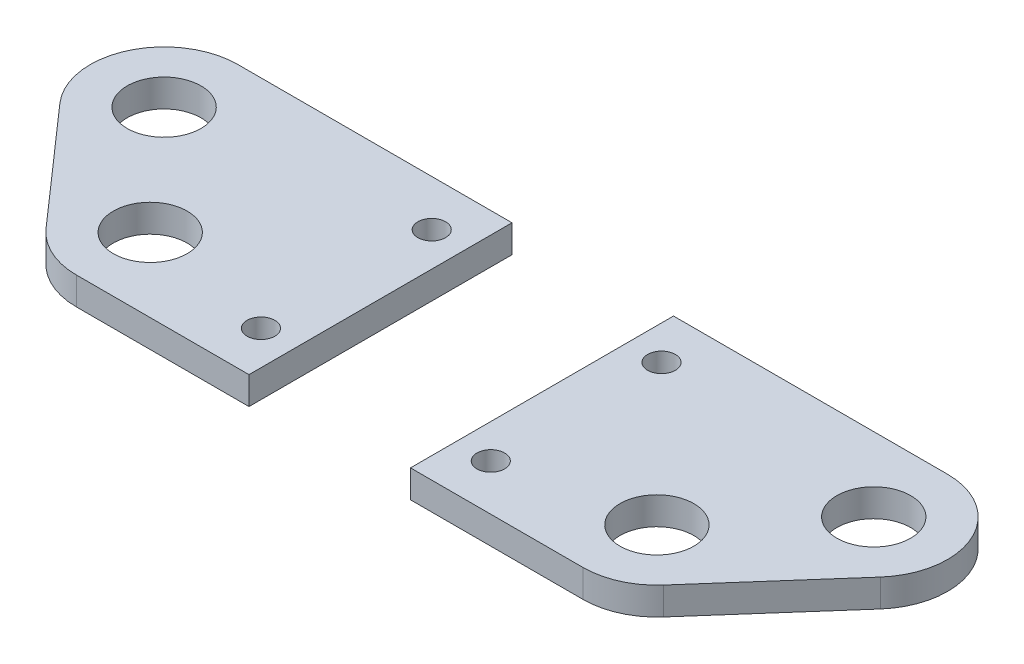
SolidWorks part; units mm, degrees
material "Chipboard"
ref_plane "Front Plane" through (0, 0, 0) normal (0, 0, 1) x (1, 0, 0)
ref_plane "Top Plane" through (0, 0, 0) normal (0, 1, 0) x (1, 0, 0)
ref_plane "Right Plane" through (0, 0, 0) normal (1, 0, 0) x (0, 0, -1)
sketch "Sketch1" plane through (0, 0, 0) normal (0, 1, 0) x (1, 0, 0)
  line L0 (-12.45, 10.75) -> (-38.45, 10.75) construction
  line L1 (-27.45, -14.25) -> (-8.75, -14.25)
  line L2 (-12.45, -10.75) -> (-27.45, -10.75) construction
  line L3 (0, 6.25) -> (0, -6.6749) construction
  line L4 (12.45, 9.25) -> (12.45, -9.25) construction
  line L5 (-8.3494, -0.3251) -> (-12.2494, -0.3251) construction
  line L6 (-8.3494, 9.25) -> (-12.45, 9.25) construction
  line L7 (8.3494, -9.25) -> (12.45, -9.25) construction
  line L8 (8.3494, 9.25) -> (12.45, 9.25) construction
  line L9 (8.3494, -0.3251) -> (12.2494, -0.3251) construction
  line L10 (-33.4557, -11.535) -> (-44.4557, 0.965)
  line L11 (12.45, -10.75) -> (27.45, -10.75) construction
  line L12 (12.45, 10.75) -> (38.45, 10.75) construction
  line L13 (8.75, 14.25) -> (8.75, -14.25)
  line L14 (-38.45, 6.25) -> (0, 6.25) construction
  line L15 (38.45, 14.25) -> (8.75, 14.25)
  line L16 (-38.45, 14.25) -> (-8.75, 14.25)
  line L17 (33.4557, -11.535) -> (44.4557, 0.965)
  line L18 (27.45, -14.25) -> (8.75, -14.25)
  line L20 (-8.75, 14.25) -> (-8.75, -14.25)
  line L22 (-8.3494, -9.25) -> (-12.45, -9.25) construction
  line L25 (-12.45, 9.25) -> (-12.45, -9.25) construction
  circle A0 centre (-12.45, 9.25) radius 1.5
  circle A1 centre (-12.45, -9.25) radius 1.5
  arc A2 (38.45, 14.25) -> (44.4557, 0.965) centre (38.45, 6.25) cw
  circle A3 centre (27.45, -6.25) radius 4.5
  circle A4 centre (38.45, 6.25) radius 4.5
  arc A5 (-33.4557, -11.535) -> (-27.45, -14.25) centre (-27.45, -6.25) ccw
  circle A6 centre (-38.45, 6.25) radius 4.5
  arc A7 (33.4557, -11.535) -> (27.45, -14.25) centre (27.45, -6.25) cw
  circle A8 centre (-27.45, -6.25) radius 4.5
  circle A9 centre (12.45, -9.25) radius 1.5
  circle A10 centre (12.45, 9.25) radius 1.5
  arc A13 (-38.45, 14.25) -> (-44.4557, 0.965) centre (-38.45, 6.25) ccw
  point P5 (-12.45, 0)
  dimension "D2" = 9
  dimension "D7" = 8
  dimension "D8" = 16
  dimension "D13" = 18.5
  dimension "D15" = 3
  dimension "D16" = 3
  dimension "D4" = 9
  dimension "D3" = 17.5
  dimension "D5" = 24.9
  dimension "D6" = 15
  dimension "D14" = 12.45
  dimension "D17" = 12.45
  dimension "D24" = 26
  dimension "D25" = 8.75
  dimension "D26" = 3.7
extrude "Boss-Extrude1" add sketch "Sketch1" along normal blind 3
sketch "Sketch2" plane through (0, 3, 0) normal (0, 1, 0) x (1, 0, 0)
  line L0 (-12.45, -4.75) -> (-8.75, -4.75)
  line L1 (-12.45, 4.75) -> (-8.75, 4.75)
  line L2 (-17.8583, 11.25) -> (-25.9502, 11.25)
  line L3 (-38.45, 14.25) -> (-12.45, 0)
  line L4 (-8.75, 14.25) -> (-38.45, 14.25)
  line L5 (-44.4557, 0.965) -> (-33.4557, -11.535)
  line L6 (-27.45, -14.25) -> (-8.75, -14.25)
  line L7 (-8.75, -14.25) -> (-8.75, 14.25)
  line L8 (-8.75, 14.25) -> (-38.45, 14.25)
  line L9 (-44.4557, 0.965) -> (-33.4557, -11.535)
  line L10 (-27.45, -14.25) -> (-8.75, -14.25)
  line L11 (-8.75, -14.25) -> (-8.75, 14.25)
  line L12 (-17.8583, -9.25) -> (-19.3877, -9.25)
  line L13 (-12.45, -13.75) -> (-8.75, -13.75)
  line L14 (0, 0) -> (0, -14.25) construction
  line L15 (26.4308, 9.3731) -> (19.0823, 5.3455)
  line L16 (-28.972, 7.3448) -> (-20.5242, 2.7148)
  line L17 (-26.4308, 9.3731) -> (-19.0823, 5.3455)
  line L18 (28.972, 7.3448) -> (20.5242, 2.7148)
  line L19 (-37.7291, 15.5654) -> (-11.7291, 1.3154) construction
  line L20 (-8.75, 11.25) -> (-38.45, 11.25) construction
  line L21 (-39.1709, 12.9346) -> (-13.1709, -1.3154) construction
  line L22 (12.45, -13.75) -> (8.75, -13.75)
  line L23 (17.8583, -9.25) -> (19.3877, -9.25)
  line L24 (8.75, -14.25) -> (8.75, 14.25)
  line L25 (27.45, -14.25) -> (8.75, -14.25)
  line L26 (44.4557, 0.965) -> (33.4557, -11.535)
  line L27 (8.75, 14.25) -> (38.45, 14.25)
  line L28 (38.45, 14.25) -> (12.45, 0)
  line L29 (17.8583, 11.25) -> (25.9502, 11.25)
  line L30 (12.45, 4.75) -> (8.75, 4.75)
  line L31 (12.45, -4.75) -> (8.75, -4.75)
  circle A0 centre (-12.45, 9.25) radius 1.5 construction
  circle A1 centre (-12.45, 9.25) radius 1.5
  arc A2 (-38.45, 14.25) -> (-44.4557, 0.965) centre (-38.45, 6.25) ccw
  arc A3 (-33.4557, -11.535) -> (-27.45, -14.25) centre (-27.45, -6.25) ccw
  arc A4 (-38.45, 14.25) -> (-44.4557, 0.965) centre (-38.45, 6.25) ccw
  arc A5 (-33.4557, -11.535) -> (-27.45, -14.25) centre (-27.45, -6.25) ccw
  circle A6 centre (-12.45, -9.25) radius 1.5 construction
  circle A7 centre (-12.45, -9.25) radius 1.5
  circle A8 centre (-27.45, -6.25) radius 4.5 construction
  circle A9 centre (-27.45, -6.25) radius 4.5
  circle A10 centre (-38.45, 6.25) radius 4.5 construction
  circle A11 centre (-38.45, 6.25) radius 4.5
  arc A12 (-16.875, 10.0682) -> (-16.6017, 7.5141) centre (-12.45, 9.25) ccw
  arc A13 (-16.875, -10.0682) -> (-12.45, -13.75) centre (-12.45, -9.25) ccw
  arc A14 (-12.45, 4.75) -> (-12.45, -4.75) centre (-12.45, 0) ccw
  arc A15 (-21.8919, -0.4961) -> (-30.0576, 1.3131) centre (-27.45, -6.25) ccw
  arc A16 (-31.7065, 10.554) -> (-35.8424, -1.3131) centre (-38.45, 6.25) ccw
  arc A17 (-16.9444, 6.3137) -> (-17.8986, 5.5113) centre (-12.45, 0) ccw
  arc A18 (-20.0271, 1.6278) -> (-20.1975, 0.1977) centre (-12.45, 0) ccw
  arc A19 (-30.4523, 6.4437) -> (-28.972, 7.3448) centre (-29.4526, 6.4679) cw
  arc A20 (-12.45, 7.75) -> (-12.45, -7.75) centre (-12.45, 0) ccw construction
  arc A21 (-25.9502, 11.25) -> (-26.4308, 9.3731) centre (-25.9502, 10.25) ccw
  arc A22 (-17.8986, 5.5113) -> (-19.0823, 5.3455) centre (-18.6017, 6.2225) cw
  arc A23 (-20.0271, 1.6278) -> (-20.5242, 2.7148) centre (-21.0048, 1.8378) ccw
  arc A24 (-16.6017, 7.5141) -> (-16.9444, 6.3137) centre (-17.5243, 7.1284) cw
  circle A25 centre (-12.45, 9.25) radius 4.5 construction
  arc A26 (-17.8583, 11.25) -> (-16.875, 10.0682) centre (-17.8583, 10.25) cw
  arc A27 (-34.6202, -2.702) -> (-35.8424, -1.3131) centre (-35.5165, -2.2585) ccw
  arc A28 (-31.2798, 2.702) -> (-30.0576, 1.3131) centre (-30.3835, 2.2585) ccw
  arc A29 (-21.8919, -0.4961) -> (-20.1975, 0.1977) centre (-21.1972, 0.2232) ccw
  arc A30 (17.8583, -9.25) -> (16.875, -10.0682) centre (17.8583, -10.25) ccw
  arc A31 (-34.6202, -2.702) -> (-20.2835, -9.8056) centre (-27.45, -6.25) ccw
  arc A32 (-31.2798, 2.702) -> (-30.4523, 6.4437) centre (-38.45, 6.25) ccw
  arc A33 (-19.3877, -9.25) -> (-20.2835, -9.8056) centre (-19.3877, -10.25) ccw
  arc A34 (-17.8583, -9.25) -> (-16.875, -10.0682) centre (-17.8583, -10.25) cw
  circle A35 centre (-12.45, -9.25) radius 4.5 construction
  arc A36 (19.3877, -9.25) -> (20.2835, -9.8056) centre (19.3877, -10.25) cw
  arc A37 (31.2798, 2.702) -> (30.4523, 6.4437) centre (38.45, 6.25) cw
  arc A38 (34.6202, -2.702) -> (20.2835, -9.8056) centre (27.45, -6.25) cw
  arc A39 (21.8919, -0.4961) -> (20.1975, 0.1977) centre (21.1972, 0.2232) cw
  arc A40 (31.2798, 2.702) -> (30.0576, 1.3131) centre (30.3835, 2.2585) cw
  arc A41 (34.6202, -2.702) -> (35.8424, -1.3131) centre (35.5165, -2.2585) cw
  arc A42 (17.8583, 11.25) -> (16.875, 10.0682) centre (17.8583, 10.25) ccw
  arc A43 (16.6017, 7.5141) -> (16.9444, 6.3137) centre (17.5243, 7.1284) ccw
  arc A44 (20.0271, 1.6278) -> (20.5242, 2.7148) centre (21.0048, 1.8378) cw
  arc A45 (17.8986, 5.5113) -> (19.0823, 5.3455) centre (18.6017, 6.2225) ccw
  arc A46 (25.9502, 11.25) -> (26.4308, 9.3731) centre (25.9502, 10.25) cw
  arc A47 (30.4523, 6.4437) -> (28.972, 7.3448) centre (29.4526, 6.4679) ccw
  arc A48 (20.0271, 1.6278) -> (20.1975, 0.1977) centre (12.45, 0) cw
  arc A49 (16.9444, 6.3137) -> (17.8986, 5.5113) centre (12.45, 0) cw
  arc A50 (31.7065, 10.554) -> (35.8424, -1.3131) centre (38.45, 6.25) cw
  arc A51 (21.8919, -0.4961) -> (30.0576, 1.3131) centre (27.45, -6.25) cw
  arc A52 (12.45, 4.75) -> (12.45, -4.75) centre (12.45, 0) cw
  arc A53 (16.875, -10.0682) -> (12.45, -13.75) centre (12.45, -9.25) cw
  arc A54 (16.875, 10.0682) -> (16.6017, 7.5141) centre (12.45, 9.25) cw
  circle A55 centre (38.45, 6.25) radius 4.5
  circle A56 centre (27.45, -6.25) radius 4.5
  circle A57 centre (12.45, -9.25) radius 1.5
  arc A58 (33.4557, -11.535) -> (27.45, -14.25) centre (27.45, -6.25) cw
  arc A59 (38.45, 14.25) -> (44.4557, 0.965) centre (38.45, 6.25) cw
  circle A60 centre (12.45, 9.25) radius 1.5
  point P50 (-7.95, 9.25)
  point P65 (-7.95, -9.25)
  dimension "D7" = 1
  dimension "D8" = 1
  dimension "D9" = 1
  dimension "D10" = 1
  dimension "D11" = 1
  dimension "D12" = 1
  dimension "D13" = 1
  dimension "D14" = 1
  dimension "D1" = 0
  dimension "D2" = 3
  dimension "D3" = 3
  dimension "D4" = 1.5
  dimension "D5" = 1.5
  dimension "D6" = 3
extrude "Cut-Extrude1" [suppressed] cut sketch "Sketch2" against normal blind 3
sketch "Sketch3" plane through (0, 3, 0) normal (0, 1, 0) x (1, 0, 0)
  circle A0 centre (-38.45, 6.25) radius 4.5 construction
  circle A1 centre (-38.45, 6.25) radius 4.5
  circle A2 centre (-27.45, -6.25) radius 4.5 construction
  circle A3 centre (-27.45, -6.25) radius 4.5
  circle A4 centre (-38.45, 6.25) radius 4
  circle A5 centre (-27.45, -6.25) radius 4
  circle A6 centre (38.45, 6.25) radius 4.5 construction
  circle A7 centre (38.45, 6.25) radius 4.5
  circle A8 centre (27.45, -6.25) radius 4.5 construction
  circle A9 centre (27.45, -6.25) radius 4.5
  circle A10 centre (27.45, -6.25) radius 4
  circle A11 centre (38.45, 6.25) radius 4
  dimension "D1" = 0.5
  dimension "D2" = 0.5
extrude "Boss-Extrude2" add sketch "Sketch3" against normal blind 3
